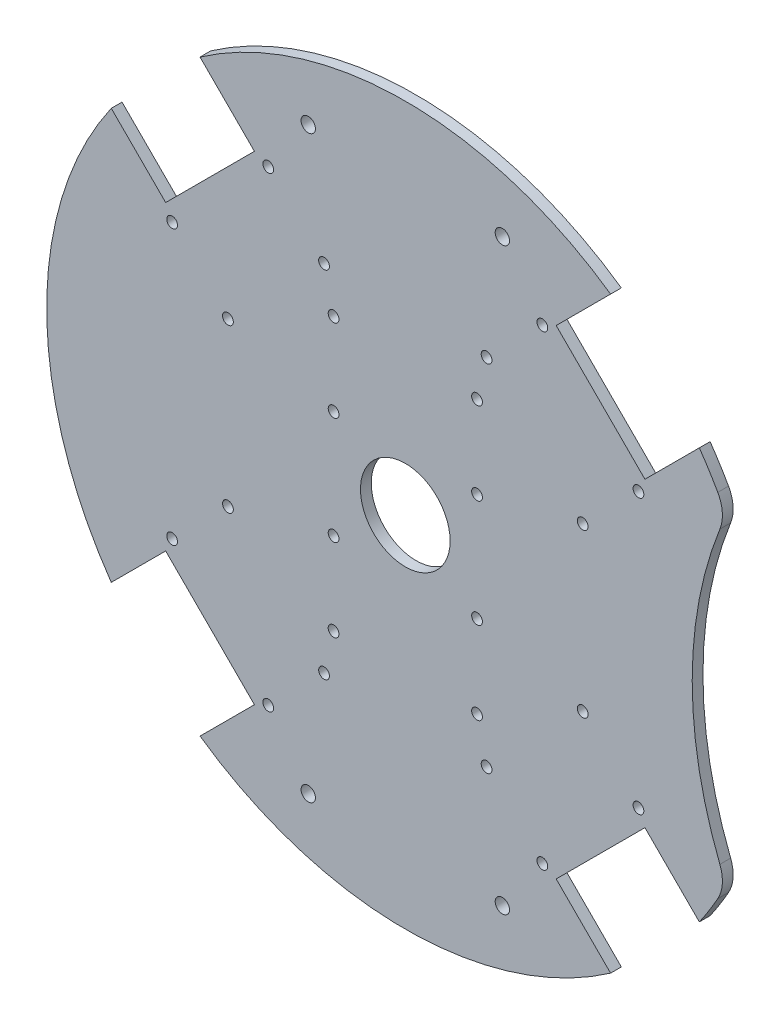
SolidWorks part; units mm, degrees
ref_plane "Alzado" through (0, 0, 0) normal (0, 0, 1) x (1, 0, 0)
ref_plane "Planta" through (0, 0, 0) normal (0, 1, 0) x (1, 0, 0)
ref_plane "Vista lateral" through (0, 0, 0) normal (1, 0, 0) x (0, 0, -1)
sketch "Croquis1" plane through (0, 0, 0) normal (0, 0, 1) x (1, 0, 0)
  circle A0 centre (0, 0) radius 100
  dimension "D1" = 200
extrude "Saliente-Extruir1" add sketch "Croquis1" along normal blind 3
sketch "Croquis3" plane through (0, 0, 3) normal (0, 0, 1) x (1, 0, 0)
  line L0 (0, 0) -> (190, 0) construction
  circle A0 centre (190, 0) radius 110
  dimension "D1" = 220
  dimension "D2" = 190
extrude "Cortar-Extruir1" cut sketch "Croquis3" against normal blind 3
fillet "Redondeo1" radius 10 2 edges at (89.4737, -44.6594, 1.5) (89.4737, 44.6594, 1.5)
sketch "Croquis4" plane through (0, 0, 3) normal (0, 0, 1) x (1, 0, 0)
  line L0 (-100, 0) -> (80, 0) construction
  line L1 (0, 0) -> (0, -100) construction
  line L2 (-54.4472, -54.4472) -> (-51.6188, -51.6188) construction
  line L3 (-58.3363, -83.085) -> (-83.085, -58.3363)
  line L4 (-66.8216, 42.0729) -> (-42.0729, 66.8216)
  line L5 (-83.085, -58.3363) -> (-66.8216, -42.0729)
  line L6 (-58.3363, -83.085) -> (-42.0729, -66.8216)
  line L7 (-42.0729, -66.8216) -> (-66.8216, -42.0729)
  line L8 (-58.3363, 83.085) -> (-42.0729, 66.8216)
  line L9 (-83.085, 58.3363) -> (-58.3363, 83.085)
  line L10 (-83.085, 58.3363) -> (-66.8216, 42.0729)
  line L11 (42.0729, 66.8216) -> (66.8216, 42.0729)
  line L12 (83.085, 58.3363) -> (66.8216, 42.0729)
  line L13 (58.3363, 83.085) -> (83.085, 58.3363)
  line L14 (58.3363, 83.085) -> (42.0729, 66.8216)
  line L15 (66.8216, -42.0729) -> (42.0729, -66.8216)
  line L16 (58.3363, -83.085) -> (42.0729, -66.8216)
  line L17 (83.085, -58.3363) -> (58.3363, -83.085)
  line L18 (83.085, -58.3363) -> (66.8216, -42.0729)
  arc A0 (87.1345, 49.0671) -> (87.1345, -49.0671) centre (0, 0) ccw construction
  arc A1 (87.7193, 40.4803) -> (87.7193, -40.4803) centre (190, 0) ccw construction
  circle A2 centre (-65.0185, -38.2191) radius 1.5
  circle A3 centre (-49.4621, -22.6628) radius 1.5
  circle A4 centre (-22.6628, -49.4621) radius 1.5
  circle A5 centre (-38.2191, -65.0185) radius 1.5
  circle A6 centre (-22.6628, 49.4621) radius 1.5
  circle A7 centre (-38.2191, 65.0185) radius 1.5
  circle A8 centre (-49.4621, 22.6628) radius 1.5
  circle A9 centre (-65.0185, 38.2191) radius 1.5
  circle A10 centre (49.4621, 22.6628) radius 1.5
  circle A11 centre (65.0185, 38.2191) radius 1.5
  circle A12 centre (22.6628, 49.4621) radius 1.5
  circle A13 centre (38.2191, 65.0185) radius 1.5
  circle A14 centre (22.6628, -49.4621) radius 1.5
  circle A15 centre (38.2191, -65.0185) radius 1.5
  circle A16 centre (49.4621, -22.6628) radius 1.5
  circle A17 centre (65.0185, -38.2191) radius 1.5
  circle A18 centre (0, 0) radius 12.5
  point P64 (0, 0)
  dimension "D5" = 3
  dimension "D6" = 3
  dimension "D7" = 3
  dimension "D8" = 22
  dimension "D9" = 3
  dimension "D10" = 37.9
  dimension "D11" = 22
  dimension "D12" = 37.9
  dimension "D14" = 54.4068
  dimension "D17" = 25
  dimension "D1" = 35
  dimension "D2" = 23
  dimension "D3" = 23
  dimension "D4" = 17.5
  dimension "D13" = 4
  dimension "D15" = 77
  dimension "D16" = 4
extrude "Cortar-Extruir2" cut sketch "Croquis4" against normal through all
sketch "Croquis5" plane through (0, 0, 0) normal (0, 0, -1) x (-1, 0, 0)
  line L0 (-20, -15) -> (-20, -38) construction
  line L1 (-20, -38) -> (20, -38) construction
  line L2 (20, -38) -> (20, -15) construction
  line L3 (0, 0) -> (12.5, 0) construction
  line L4 (0, 0) -> (0, -100) construction
  line L8 (20, -15) -> (-20, -15) construction
  circle A0 centre (0, 0) radius 12.5 construction
  circle A1 centre (-20, -38) radius 1.5
  circle A2 centre (-20, -15) radius 1.5
  circle A3 centre (20, -15) radius 1.5
  circle A4 centre (20, -38) radius 1.5
  arc A5 (-57.2451, -81.9939) -> (57.2451, -81.9939) centre (0, 0) ccw construction
  circle A6 centre (-20, 15) radius 1.5
  circle A7 centre (-20, 38) radius 1.5
  circle A8 centre (20, 38) radius 1.5
  circle A9 centre (20, 15) radius 1.5
  point P41 (0, 0)
  point P59 (0, 0)
  dimension "D1" = 23
  dimension "D8" = 20
  dimension "D3" = 3
  dimension "D4" = 3
  dimension "D5" = 3
  dimension "D6" = 3
  dimension "D7" = 46.1411
  dimension "D2" = 15
extrude "Cortar-Extruir3" cut sketch "Croquis5" against normal through all
sketch "Croquis7" plane through (0, 0, 0) normal (0, 0, -1) x (-1, 0, 0)
  line L0 (0, 0) -> (0, -87.26) construction
  line L1 (33.54, -87.26) -> (-33.54, -87.26) construction
  line L2 (33.54, -87.26) -> (33.54, -74.31) construction
  line L3 (33.54, -74.31) -> (20.59, -74.31) construction
  line L4 (-33.54, -87.26) -> (-33.54, -74.31) construction
  line L5 (-33.54, -74.31) -> (-20.59, -74.31) construction
  line L6 (-20.59, -74.31) -> (-33.54, -87.26) construction
  line L7 (20.59, -74.31) -> (33.54, -87.26) construction
  line L10 (-12.5, 0) -> (12.5, 0) construction
  circle A0 centre (-27.065, -80.785) radius 2
  circle A1 centre (27.065, -80.785) radius 2
  circle A3 centre (0, 0) radius 12.5 construction
  circle A4 centre (27.065, 80.785) radius 2
  circle A5 centre (-27.065, 80.785) radius 2
  dimension "D1" = 4
  dimension "D2" = 4
  dimension "D6" = 6.475
  dimension "D7" = 6.475
  dimension "D4" = 18.3141
  dimension "D5" = 18.3141
extrude "Cortar-Extruir5" cut sketch "Croquis7" against normal blind 10
